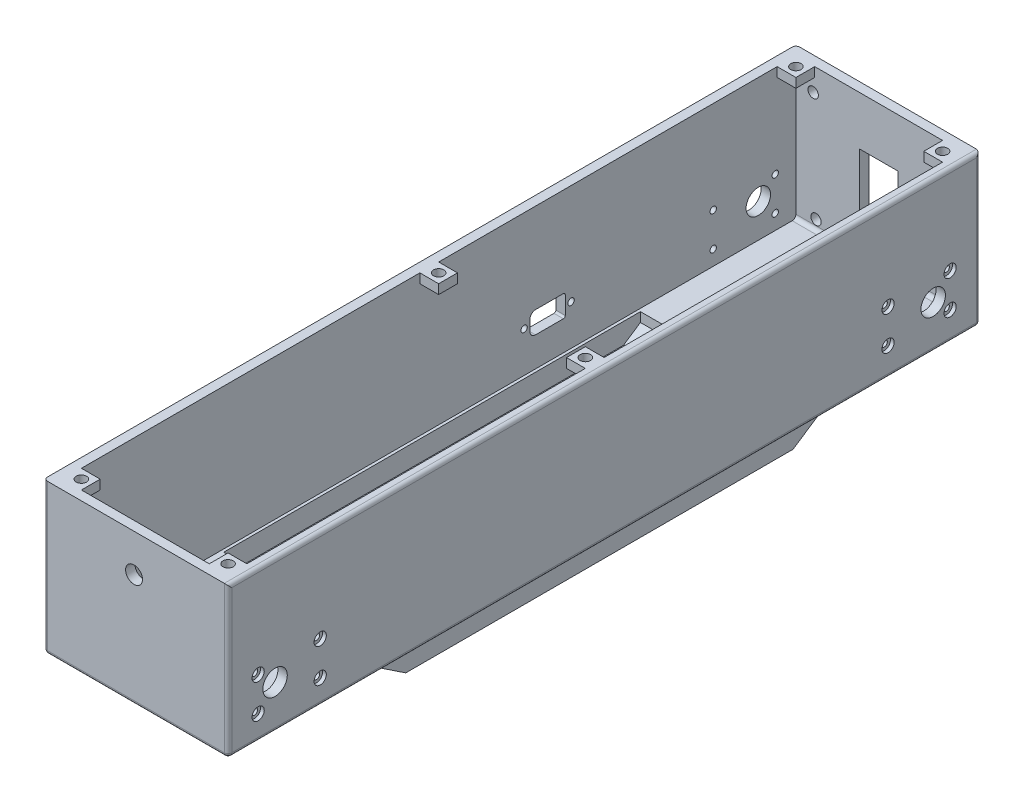
SolidWorks part; units mm, degrees
material "6061-O (SS)"
ref_plane "Alzado" through (0, 0, 0) normal (0, 0, 1) x (1, 0, 0)
ref_plane "Planta" through (0, 0, 0) normal (0, 1, 0) x (1, 0, 0)
ref_plane "Vista lateral" through (0, 0, 0) normal (1, 0, 0) x (0, 0, -1)
sketch "Croquis1" plane through (0, 0, 0) normal (0, 0, 1) x (1, 0, 0)
  line L1 (-49, -40) -> (49, -40)
  line L2 (-49, -40) -> (-49, 40)
  line L3 (-49, 40) -> (49, 40)
  line L4 (49, -40) -> (49, 40)
  point P4 (0, 40)
  point P6 (-49, 0)
  dimension "D1" = 80
  dimension "D2" = 98
extrude "Saliente-Extruir1" add sketch "Croquis1" along normal mid plane 400
shell "Vaciado1" thickness 5
fillet "Redondeo1" radius 2 11 edges at (49, -40, 0) (49, 0, 200) (49, 40, 0) (49, 0, -200) (0, -40, -200) (-49, 0, -200) (-49, -40, 0) (-49, 0, 200) (0, -40, 200) (0, -35, 195) (0, -35, -195)
sketch "Croquis3" plane through (-49, 0, 0) normal (-1, 0, 0) x (0, 0, 1)
  line L4 (198, 40) -> (-198, 40)
  line L5 (-198, 40) -> (-198, -38)
  line L6 (-198, -38) -> (198, -38)
  line L7 (198, -38) -> (198, 40)
  line L8 (198, 40) -> (-198, 40)
  line L11 (198, -38) -> (198, 40)
  line L12 (-144, -35) -> (-144, -1) construction
  line L13 (-184, -27.06) -> (-151, -27.06) construction
  line L14 (-184, -27.06) -> (-184, -9.06) construction
  line L15 (-184, -9.06) -> (-151, -9.06) construction
  line L16 (-151, -27.06) -> (-151, -9.06) construction
  line L70 (-144, -1) -> (-190, -1) construction
  line L71 (-190, -1) -> (-190, -35) construction
  line L72 (-198, -38) -> (198, -38) construction
  line L92 (-200, -38) -> (-200, 40) construction
  line L117 (-190, -35) -> (-144, -35) construction
  point P1 (-198, 40)
  point P12 (-184, -9.06)
  point P13 (-151, -9.06)
  point P14 (-151, -27.06)
  point P15 (-184, -27.06)
  point P193 (-201.1346, -38)
  point P286 (-184, -18.06)
  dimension "D2" = 33
  dimension "D3" = 10
  dimension "D4" = 6
  dimension "D5" = 46
  dimension "D6" = 18
  dimension "D7" = 10
  dimension "D9" = 3
  dimension "D10" = 17.06
  dimension "D1" = 0
sketch "Croquis5" plane through (0, 0, -200) normal (0, 0, -1) x (-1, 0, 0)
  line L5 (0, 0) -> (69.6678, 55.4163) construction
  line L6 (0, 52.16) -> (0, -52.16) construction
  line L7 (-76.4408, 0) -> (76.4408, 0) construction
  line L9 (0, 0) -> (66.6304, -59.9943) construction
  line L14 (0, 0) -> (-66.6304, -59.9943) construction
  line L15 (0, 0) -> (-69.6678, 55.4163) construction
  circle A5 centre (0, 0) radius 44.51 construction
  circle A6 centre (0, 0) radius 44.83 construction
  point P33 (0, 0)
  point P65 (0, 0)
  point P103 (34.8339, 27.7081)
  point P106 (0, 0)
  point P114 (33.3152, -29.9971)
  point P117 (-33.3152, -29.9971)
  point P120 (-34.8339, 27.7081)
  dimension "D4" = 48
  dimension "D2" = 89.02
  dimension "D1" = 89.66
  dimension "D3" = 38.5
sketch "Croquis6" plane through (0, 0, 195) normal (0, 0, -1) x (-1, 0, 0)
  line L0 (-44, 40) -> (44, 40) construction
  line L1 (-44, -33) -> (-44, 40) construction
  circle A0 centre (1, 20) radius 4.5
  dimension "D1" = 9
  dimension "D2" = 20
  dimension "D3" = 45
extrude "Cortar-Extruir3" cut sketch "Croquis6" against normal through all
hole_wizard "Refrentado para tornillo con cabeza plana de M31" positions "Croquis3" profile "Croquis8" counterbore size "M3" standard "BSI"
sketch "Croquis8" plane through (-49, -27.06, -184) normal (0, 1, 0) x (0, 0, 1)
  line L0 (0, 0) -> (0, 5)
  line L1 (0, 5) -> (1.7, 5)
  line L3 (1.7, 5) -> (1.7, 2)
  line L4 (1.7, 2) -> (3.25, 2)
  line L5 (3.25, 2) -> (3.25, 0)
  line L7 (3.25, 0) -> (0, 0)
  line L11 (0, -6.35) -> (0, 107.95) construction
  dimension "Diámetro de taladro hasta el siguiente" = 3.4
  dimension "Profundidad de taladro hasta el siguiente" = 5
  dimension "Diámetro de refrentado" = 6.5
  dimension "Profundidad de refrentado" = 2
sketch "Croquis11" plane through (-49, 0, 0) normal (-1, 0, 0) x (0, 0, 1)
  circle A0 centre (-175, -17.06) radius 6.5
  dimension "D1" = 13
extrude "Cortar-Extruir5" cut sketch "Croquis11" against normal up to next
mirror "Simetría3" about plane through (0, 0, 0) normal (0, 0, 1) of "Cortar-Extruir5" second plane through (0, 0, 0) second plane normal (1, 0, 0)
sketch "Croquis12" plane through (-49, 0, 0) normal (-1, 0, 0) x (0, 0, 1)
  line L0 (151, -7.06) -> (151, -25.06) construction
  line L1 (151, -25.06) -> (184, -25.06) construction
  line L2 (184, -25.06) -> (184, -7.06) construction
  line L3 (184, -7.06) -> (151, -7.06) construction
  line L4 (144, -2) -> (144, -34) construction
  line L5 (144, -34) -> (190, -34) construction
  line L6 (190, -34) -> (190, -2) construction
  line L7 (190, -2) -> (144, -2) construction
  line L8 (200, 40) -> (200, -38) construction
  line L9 (198, -40) -> (-198, -40) construction
  circle A0 centre (175, -17.06) radius 6.5 construction
  circle A1 centre (175, -17.06) radius 6.5
  point P16 (151, -7.06)
  point P17 (184, -7.06)
  point P18 (184, -25.06)
  point P19 (151, -25.06)
  dimension "D1" = 18
  dimension "D2" = 32
  dimension "D3" = 46
  dimension "D4" = 33
  dimension "D5" = 10
  dimension "D6" = 10
  dimension "D7" = 6
  dimension "D8" = 6
hole_wizard "Refrentado para tornillo con cabeza plana de M32" positions "Croquis12" profile "Croquis13" counterbore size "M3" standard "BSI"
sketch "Croquis13" plane through (-49, -25.06, 151) normal (0, 1, 0) x (0, 0, 1)
  line L0 (0, 0) -> (0, 5)
  line L1 (0, 5) -> (1.7, 5)
  line L3 (1.7, 5) -> (1.7, 2)
  line L4 (1.7, 2) -> (3.25, 2)
  line L5 (3.25, 2) -> (3.25, 0)
  line L7 (3.25, 0) -> (0, 0)
  line L11 (0, -6.35) -> (0, 107.95) construction
  dimension "Diámetro de taladro hasta el siguiente" = 3.4
  dimension "Profundidad de taladro hasta el siguiente" = 5
  dimension "Diámetro de refrentado" = 6.5
  dimension "Profundidad de refrentado" = 2
sketch "Croquis14" plane through (49, 0, 0) normal (1, 0, 0) x (0, 0, -1)
  line L0 (-184, -9.06) -> (-184, -27.06) construction
  line L1 (-184, -27.06) -> (-151, -27.06) construction
  line L2 (-151, -27.06) -> (-151, -9.06) construction
  line L3 (-151, -9.06) -> (-184, -9.06) construction
  circle A0 centre (-175, -17.06) radius 6.5 construction
  circle A1 centre (-175, -17.06) radius 6.5
  point P8 (-184, -9.06)
  point P9 (-184, -27.06)
  point P10 (-151, -27.06)
  point P11 (-151, -9.06)
  dimension "D1" = 18
  dimension "D2" = 33
  dimension "D3" = 10
  dimension "D4" = 9
hole_wizard "Refrentado para tornillo con cabeza plana de M33" positions "Croquis14" profile "Croquis17" counterbore size "M3" standard "BSI"
sketch "Croquis17" plane through (49, -9.06, 151) normal (0, 1, 0) x (0, 0, -1)
  line L0 (0, 0) -> (0, 5)
  line L1 (0, 5) -> (1.7, 5)
  line L3 (1.7, 5) -> (1.7, 2)
  line L4 (1.7, 2) -> (3.25, 2)
  line L5 (3.25, 2) -> (3.25, 0)
  line L7 (3.25, 0) -> (0, 0)
  line L11 (0, -6.35) -> (0, 107.95) construction
  dimension "Diámetro de taladro hasta el siguiente" = 3.4
  dimension "Profundidad de taladro hasta el siguiente" = 5
  dimension "Diámetro de refrentado" = 6.5
  dimension "Profundidad de refrentado" = 2
sketch "Croquis18" plane through (49, 0, 0) normal (1, 0, 0) x (0, 0, -1)
  line L0 (151, -7.06) -> (151, -25.06) construction
  line L1 (151, -25.06) -> (184, -25.06) construction
  line L2 (184, -25.06) -> (184, -7.06) construction
  line L3 (184, -7.06) -> (151, -7.06) construction
  circle A0 centre (175, -17.06) radius 6.5 construction
  circle A1 centre (175, -17.06) radius 6.5
  point P8 (151, -7.06)
  point P9 (184, -7.06)
  point P10 (184, -25.06)
  point P11 (151, -25.06)
  dimension "D1" = 18
  dimension "D2" = 33
  dimension "D3" = 8
  dimension "D4" = 9
hole_wizard "Refrentado para tornillo con cabeza plana de M34" positions "Croquis18" profile "Croquis19" counterbore size "M3" standard "BSI"
sketch "Croquis19" plane through (49, -25.06, -151) normal (0, 1, 0) x (0, 0, -1)
  line L0 (0, 0) -> (0, 5)
  line L1 (0, 5) -> (1.6, 5)
  line L3 (1.6, 5) -> (1.6, 2)
  line L4 (1.6, 2) -> (3.25, 2)
  line L5 (3.25, 2) -> (3.25, 0)
  line L7 (3.25, 0) -> (0, 0)
  line L11 (0, -6.35) -> (0, 107.95) construction
  dimension "Diámetro de taladro hasta el siguiente" = 3.2
  dimension "Profundidad de taladro hasta el siguiente" = 5
  dimension "Diámetro de refrentado" = 6.5
  dimension "Profundidad de refrentado" = 2
sketch "Croquis21" plane through (0, 0, -200) normal (0, 0, -1) x (-1, 0, 0)
  line L0 (-10.25, -27) -> (10.25, -27)
  line L1 (-10.25, -27) -> (-10.25, 14)
  line L2 (-10.25, 14) -> (10.25, 14)
  line L3 (10.25, -27) -> (10.25, 14)
  point P4 (0, -27)
  dimension "D1" = 41
  dimension "D2" = 20.5
  dimension "D3" = 27
extrude "Cortar-Extruir6" cut sketch "Croquis21" against normal blind 10 contours L0 L3 L2 L1
sketch "Croquis23" plane through (0, 0, 0) normal (1, 0, 0) x (0, 0, -1)
  line L0 (-118, -40) -> (-103, -50)
  line L1 (198, -40) -> (-198, -40) construction
  line L2 (-103, -50) -> (103, -50)
  line L3 (103, -50) -> (118, -40)
  line L4 (-198, 38) -> (-198, -38) construction
  line L5 (198, -38) -> (198, 38) construction
  line L6 (-110.7889, -40) -> (-101.7889, -46)
  line L7 (-101.7889, -46) -> (101.7889, -46)
  line L8 (101.7889, -46) -> (110.7889, -40)
  line L9 (118, -40) -> (110.7889, -40)
  line L10 (-198, -40) -> (198, -40) construction
  line L11 (-118, -40) -> (-110.7889, -40)
  line L12 (-115.7812, -36.6718) -> (-101.7889, -46) construction
  line L13 (101.7889, -46) -> (115.7812, -36.6718) construction
  dimension "D1" = 10
  dimension "D2" = 15
  dimension "D3" = 80
  dimension "D4" = 80
  dimension "D5" = 4
extrude "Saliente-Extruir2" add sketch "Croquis23" along normal mid plane 85
sketch "Croquis24" plane through (0, -40, 0) normal (0, -1, 0) x (1, 0, 0)
  line L0 (42.5, 110.7889) -> (-42.5, 110.7889) construction
  line L1 (42.5, -110.7889) -> (-42.5, -110.7889) construction
  line L2 (42.5, 110.7889) -> (-42.5, 110.7889)
  line L3 (42.5, -110.7889) -> (-42.5, -110.7889)
  line L4 (-42.5, 110.7889) -> (-42.5, -110.7889)
  line L5 (42.5, -110.7889) -> (42.5, 110.7889)
extrude "Cortar-Extruir7" cut sketch "Croquis24" against normal up to next
sketch "Croquis25" plane through (42.5, 0, 0) normal (1, 0, 0) x (0, 0, -1)
  line L7 (103, -50) -> (118, -40) construction
  line L8 (-103, -50) -> (103, -50) construction
  line L9 (-118, -40) -> (-103, -50) construction
  line L10 (103, -50) -> (118, -40)
  line L11 (-103, -50) -> (103, -50)
  line L12 (-118, -40) -> (-103, -50)
  line L13 (-118, -40) -> (118, -40)
extrude "Saliente-Extruir7" add sketch "Croquis25" along normal blind 4
mirror "Simetría4" about plane through (0, 0, 0) normal (1, 0, 0) of "Saliente-Extruir7"
sketch "Croquis26" plane through (-49, 0, 0) normal (-1, 0, 0) x (0, 0, 1)
  line L2 (-72.325, -8.7) -> (-72.325, -18.3)
  line L3 (-71.325, -19.3) -> (-56.525, -19.3)
  line L4 (198, 40) -> (-198, 40)
  line L5 (-198, 40) -> (-198, -38)
  line L6 (-198, -38) -> (198, -38)
  line L7 (198, -38) -> (198, 40)
  line L8 (198, 40) -> (-198, 40)
  line L9 (-198, 40) -> (-198, -38)
  line L10 (-198, -38) -> (198, -38)
  line L11 (198, -38) -> (198, 40)
  line L12 (-53.525, -16.3) -> (-53.525, -10.7)
  line L14 (-71.325, -7.7) -> (-56.525, -7.7)
  arc A0 (-71.325, -19.3) -> (-72.325, -18.3) centre (-71.325, -18.3) cw
  arc A1 (-71.325, -7.7) -> (-72.325, -8.7) centre (-71.325, -8.7) ccw
  arc A2 (-53.525, -16.3) -> (-56.525, -19.3) centre (-56.525, -16.3) cw
  arc A3 (-53.525, -10.7) -> (-56.525, -7.7) centre (-56.525, -10.7) ccw
  point P7 (-72.325, -19.3)
  point P16 (-72.325, -7.7)
  point P19 (-53.525, -19.3)
  dimension "D4" = 1
  dimension "D6" = 3
  dimension "D2" = 11.6
  dimension "D3" = 18.8
  dimension "D5" = 125.675
  dimension "D1" = 0
extrude "Cortar-Extruir8" cut sketch "Croquis26" against normal up to next contours A3 L12 A2 L3 A0 L2 A1 L14
sketch "Croquis27" plane through (-49, 0, 0) normal (-1, 0, 0) x (0, 0, 1)
  circle A0 centre (-75.425, -13.5) radius 1.55
  circle A1 centre (-50.425, -13.5) radius 1.55
  point P9 (-75.425, -13.5)
  point P10 (-50.425, -13.5)
hole_wizard "Taladro de margen para M31" positions "Croquis27" profile "Croquis28" hole size "M3" standard "Ansi Metric"
sketch "Croquis28" plane through (-49, -13.5, -50.425) normal (0, 1, 0) x (0, 0, 1)
  line L0 (0, 0) -> (0, 5)
  line L1 (0, 5) -> (1.7, 5)
  line L2 (1.7, 5) -> (1.7, 0)
  line L5 (1.7, 0) -> (0, 0)
  line L11 (0, -6.35) -> (0, 107.95) construction
  dimension "Diámetro de taladro hasta el siguiente" = 3.4
  dimension "Profundidad de taladro hasta el siguiente" = 5
hole_wizard "Taladro de margen para M51" positions "Croquis5" profile "Croquis29" hole size "M5" standard "BSI" end condition up to next
sketch "Croquis29" plane through (34.8339, 27.7081, -200) normal (1, 0, 0) x (0, 1, 0)
  line L0 (0, 0) -> (0, 5)
  line L1 (0, 5) -> (2.75, 5)
  line L2 (2.75, 5) -> (2.75, 0)
  line L5 (2.75, 0) -> (0, 0)
  line L11 (0, -6.35) -> (0, 107.95) construction
  dimension "Diámetro de taladro hasta el siguiente" = 5.5
  dimension "Profundidad de taladro hasta el siguiente" = 5
sketch "Croquis30" plane through (0, 40, 0) normal (0, 1, 0) x (1, 0, 0)
  line L0 (44, -195) -> (-44, -195) construction
  line L1 (-44, 195) -> (44, 195) construction
  line L2 (44, -195) -> (44, 195) construction
  line L3 (-44, -195) -> (-44, 195) construction
  line L4 (44, -195) -> (-44, -195)
  line L5 (-44, 195) -> (44, 195)
  line L6 (44, -195) -> (44, -185)
  line L7 (-44, -195) -> (-44, -185)
  line L8 (34, -195) -> (34, -185)
  line L9 (34, -185) -> (44, -185)
  line L10 (-44, -185) -> (-34, -185)
  line L11 (-34, -185) -> (-34, -195)
  line L12 (-34, 195) -> (-34, 185)
  line L13 (-34, 185) -> (-44, 185)
  line L14 (34, 195) -> (34, 185)
  line L15 (34, 185) -> (44, 185)
  line L16 (-44, 5) -> (-34, 5)
  line L17 (-34, 5) -> (-34, -5)
  line L18 (-34, -5) -> (-44, -5)
  line L19 (44, 5) -> (34, 5)
  line L20 (34, 5) -> (34, -5)
  line L21 (34, -5) -> (44, -5)
  line L22 (-44, -5) -> (-44, 5)
  line L23 (44, -5) -> (44, 5)
  line L24 (-44, 185) -> (-44, 195)
  line L25 (44, 185) -> (44, 195)
  point P22 (-34, 0)
  point P25 (0, 0)
  point P27 (0, 0)
  point P28 (0, 0)
  point P29 (0, 0)
  line M19 (-44, 195) -> (44, 195)
  line M20 (44, 195) -> (44, -195)
  line M21 (44, -195) -> (-44, -195)
  line M22 (-44, -195) -> (-44, 195)
  dimension "D1" = 10
  dimension "D2" = 10
extrude "Saliente-Extruir8" add sketch "Croquis30" against normal blind 5 contours L14 L15 M20 M19 | L13 L12 M19 M22 | L11 L10 M22 M21 | L9 L8 L6 M21 | L21 L23 L19 L20 | L18 L22 L16 L17
sketch "Croquis31" plane through (0, 40, 0) normal (0, 1, 0) x (1, 0, 0)
  line L20 (34, -195) -> (34, -185)
  line L21 (-34, -195) -> (34, -195)
  line L22 (-34, -185) -> (-34, -195)
  line L23 (-44, -185) -> (-34, -185)
  line L24 (-44, -5) -> (-44, -185)
  line L25 (-34, -5) -> (-44, -5)
  line L26 (-34, 5) -> (-34, -5)
  line L27 (-44, 5) -> (-34, 5)
  line L28 (-44, 185) -> (-44, 5)
  line L29 (-34, 185) -> (-44, 185)
  line L30 (-34, 195) -> (-34, 185)
  line L31 (34, 195) -> (-34, 195)
  line L32 (34, 185) -> (34, 195)
  line L33 (44, 185) -> (34, 185)
  line L34 (44, 5) -> (44, 185)
  line L35 (34, 5) -> (44, 5)
  line L36 (34, -5) -> (34, 5)
  line L37 (44, -5) -> (34, -5)
  line L38 (44, -185) -> (44, -5)
  line L39 (34, -185) -> (44, -185)
  line L40 (34, -195) -> (34, -185)
  line L41 (-34, -195) -> (34, -195)
  line L42 (-34, -185) -> (-34, -195)
  line L43 (-44, -185) -> (-34, -185)
  line L44 (-44, -5) -> (-44, -185)
  line L45 (-34, -5) -> (-44, -5)
  line L46 (-34, 5) -> (-34, -5)
  line L47 (-44, 5) -> (-34, 5)
  line L48 (-44, 185) -> (-44, 5)
  line L49 (-34, 185) -> (-44, 185)
  line L50 (-34, 195) -> (-34, 185)
  line L51 (34, 195) -> (-34, 195)
  line L52 (34, 185) -> (34, 195)
  line L53 (44, 185) -> (34, 185)
  line L54 (44, 5) -> (44, 185)
  line L55 (34, 5) -> (44, 5)
  line L56 (34, -5) -> (34, 5)
  line L57 (44, -5) -> (34, -5)
  line L58 (44, -185) -> (44, -5)
  line L59 (34, -185) -> (44, -185)
  line L80 (-49, -198) -> (-49, 198) construction
  line L81 (47, 200) -> (-47, 200) construction
  point P2 (-39, 190)
  point P4 (39, 0)
  point P6 (-34, 190)
  point P8 (-39, 185)
  point P10 (39, 190)
  point P12 (-39, 0)
  point P14 (39, -190)
  point P16 (-39, -190)
  point P20 (34, 190)
  point P24 (39, 185)
  point P28 (34, 0)
  point P32 (39, -5)
  point P36 (-34, 0)
  point P38 (-39, -5)
  point P40 (39, -185)
  point P42 (34, -190)
  dimension "D2" = 10
  dimension "D3" = 10
  dimension "D1" = 0
hole_wizard "Taladro de margen para M52" positions "Croquis31" profile "Croquis32" hole size "M5" standard "BSI"
sketch "Croquis32" plane through (-39, 40, 190) normal (1, 0, 0) x (0, 0, 1)
  line L0 (0, 0) -> (0, 5)
  line L1 (0, 5) -> (2.75, 5)
  line L2 (2.75, 5) -> (2.75, 0)
  line L5 (2.75, 0) -> (0, 0)
  line L11 (0, -6.35) -> (0, 107.95) construction
  dimension "Diámetro de taladro hasta el siguiente" = 5.5
  dimension "Profundidad de taladro hasta el siguiente" = 5
